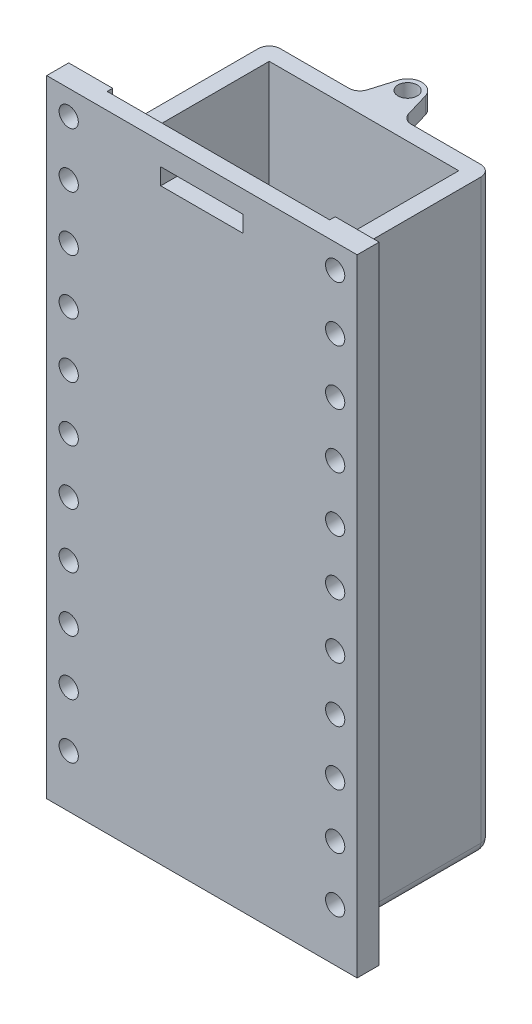
SolidWorks part; units mm, degrees
ref_plane "Alzado" through (0, 0, 0) normal (0, 0, 1) x (1, 0, 0)
ref_plane "Planta" through (0, 0, 0) normal (0, 1, 0) x (1, 0, 0)
ref_plane "Vista lateral" through (0, 0, 0) normal (1, 0, 0) x (0, 0, -1)
sketch "Croquis1" plane through (0, 0, 0) normal (0, 1, 0) x (1, 0, 0)
  line L0 (0, 0) -> (-28.25, 0)
  line L1 (-28.25, 0) -> (-28.25, 4)
  line L2 (-28.25, 4) -> (-20.25, 4)
  line L3 (-20.25, 4) -> (-20.25, 32.5)
  line L4 (-20.25, 32.5) -> (20.25, 32.5)
  line L5 (20.25, 32.5) -> (20.25, 4)
  line L6 (20.25, 4) -> (28.25, 4)
  line L7 (28.25, 4) -> (28.25, 0)
  line L8 (28.25, 0) -> (0, 0)
  dimension "D1" = 8
  dimension "D2" = 40.5
  dimension "D3" = 32.5
  dimension "D4" = 4
extrude "Saliente-Extruir1" add sketch "Croquis1" along normal blind 114
sketch "Croquis3" plane through (0, 114, 0) normal (0, 1, 0) x (1, 0, 0)
  line L0 (20.25, 32.5) -> (-20.25, 32.5) construction
  line L1 (-17.25, 29.5) -> (17.25, 29.5)
  line L2 (-17.25, 29.5) -> (-17.25, 3)
  line L3 (-17.25, 3) -> (17.25, 3)
  line L4 (17.25, 29.5) -> (17.25, 3)
  line L5 (-20.25, 32.5) -> (-20.25, 4) construction
  line L6 (-28.25, 0) -> (28.25, 0) construction
  line L7 (20.25, 4) -> (20.25, 32.5) construction
  dimension "D1" = 3
  dimension "D2" = 3
  dimension "D3" = 3
  dimension "D4" = 3
extrude "Cortar-Extruir1" cut sketch "Croquis3" against normal blind 111
sketch "Croquis4" plane through (0, 0, -32.5) normal (0, 0, -1) x (-1, 0, 0)
  line L0 (20.25, 114) -> (20.25, 0) construction
  line L1 (-20.25, 114) -> (20.25, 114)
  line L2 (-20.25, 114) -> (-20.25, 107)
  line L3 (-20.25, 107) -> (20.25, 107)
  line L4 (20.25, 114) -> (20.25, 107)
  dimension "D1" = 7
extrude "Cortar-Extruir2" cut sketch "Croquis4" against normal blind 29.5
sketch "Croquis5" plane through (0, 0, -3) normal (0, 0, -1) x (-1, 0, 0)
  line L0 (-20.25, 107) -> (20.25, 107) construction
  line L1 (-7.5, 107) -> (7.5, 107)
  line L2 (-7.5, 107) -> (-7.5, 110)
  line L3 (-7.5, 110) -> (7.5, 110)
  line L4 (7.5, 107) -> (7.5, 110)
  line L5 (-20.25, 114) -> (-20.25, 107) construction
  dimension "D1" = 15
  dimension "D2" = 3
  dimension "D3" = 12.75
extrude "Cortar-Extruir3" cut sketch "Croquis5" against normal through all
sketch "Croquis6" plane through (0, 0, -4) normal (0, 0, -1) x (-1, 0, 0)
  line L0 (-24.25, 114) -> (-24.25, -6.9854) construction
  line L1 (-28.25, 114) -> (-20.25, 114) construction
  line L2 (0, 0) -> (0, 120.6306) construction
  circle A0 centre (-24.25, 109.5526) radius 1.75
  circle A1 centre (-24.25, 99.5526) radius 1.75
  circle A2 centre (-24.25, 89.5526) radius 1.75
  circle A3 centre (-24.25, 79.5526) radius 1.75
  circle A4 centre (-24.25, 69.5526) radius 1.75
  circle A5 centre (-24.25, 59.5526) radius 1.75
  circle A6 centre (-24.25, 49.5526) radius 1.75
  circle A7 centre (-24.25, 39.5526) radius 1.75
  circle A8 centre (-24.25, 29.5526) radius 1.75
  circle A9 centre (-24.25, 19.5526) radius 1.75
  circle A10 centre (-24.25, 9.5526) radius 1.75
  circle A11 centre (24.25, 9.5526) radius 1.75
  circle A12 centre (24.25, 19.5526) radius 1.75
  circle A13 centre (24.25, 29.5526) radius 1.75
  circle A14 centre (24.25, 39.5526) radius 1.75
  circle A15 centre (24.25, 49.5526) radius 1.75
  circle A16 centre (24.25, 59.5526) radius 1.75
  circle A17 centre (24.25, 69.5526) radius 1.75
  circle A18 centre (24.25, 79.5526) radius 1.75
  circle A19 centre (24.25, 89.5526) radius 1.75
  circle A20 centre (24.25, 99.5526) radius 1.75
  circle A21 centre (24.25, 109.5526) radius 1.75
  dimension "D1" = 3.5
  dimension "D2" = 11
extrude "Cortar-Extruir4" cut sketch "Croquis6" against normal through all
sketch "Croquis7" plane through (0, 107, 0) normal (0, 1, 0) x (1, 0, 0)
  line L0 (0, 0) -> (0, 42.3275) construction
  line L1 (-4.2578, 32.5) -> (-2.5506, 38.2392)
  line L2 (20.25, 32.5) -> (-20.25, 32.5) construction
  line L3 (2.4195, 38.2392) -> (4.1267, 32.5)
  line L4 (4.1267, 32.5) -> (-4.2578, 32.5)
  arc A0 (-2.5506, 38.2392) -> (2.4195, 38.2392) centre (-0.0655, 37.5) cw
  dimension "D1" = 5
extrude "Saliente-Extruir2" add sketch "Croquis7" against normal blind 3
sketch "Croquis8" plane through (0, 107, 0) normal (0, 1, 0) x (1, 0, 0)
  circle A0 centre (-0.0655, 37.5) radius 1.75
  dimension "D1" = 3.5
extrude "Cortar-Extruir5" cut sketch "Croquis8" against normal through all
fillet "Redondeo1" radius 2 8 edges at (-17.25, 3, -16.25) (20.25, 0, -18.25) (0, 0, -32.5) (20.25, 53.5, -32.5) (-20.25, 53.5, -32.5) (-0.0655, 104, -32.5) (-4.2578, 105.5, -32.5) (4.1267, 105.5, -32.5)
